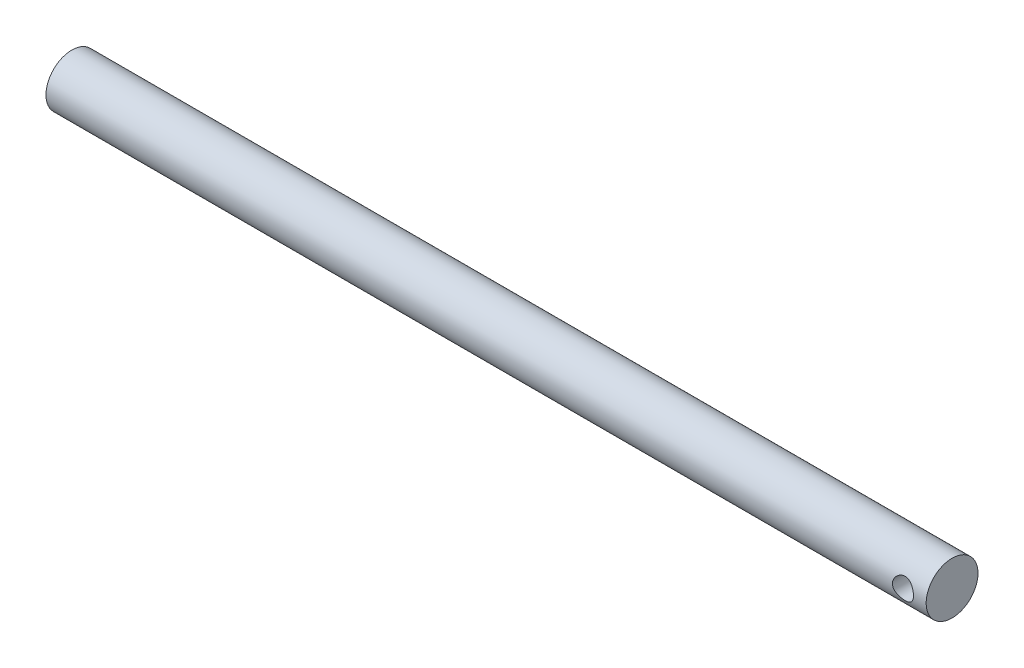
SolidWorks part; units mm, degrees
ref_plane "Front Plane" through (0, 0, 0) normal (0, 0, 1) x (1, 0, 0)
ref_plane "Top Plane" through (0, 0, 0) normal (0, 1, 0) x (1, 0, 0)
ref_plane "Right Plane" through (0, 0, 0) normal (1, 0, 0) x (0, 0, -1)
sketch "Sketch1" plane through (0, 0, 0) normal (1, 0, 0) x (0, 0, -1)
  circle A0 centre (0, 0) radius 9.906
  dimension "D1" = 19.812
extrude "Boss-Extrude1" add sketch "Sketch1" along normal blind 336.55
sketch "Sketch2" plane through (336.55, 0, 0) normal (1, 0, 0) x (0, 0, -1)
  line L0 (-9.906, 0) -> (0, 0)
  circle A0 centre (0, 0) radius 9.906 construction
  point P0 (-9.906, 0)
  point P3 (0, 0)
ref_plane "Plane1" through (336.55, 0, 9.906) normal (0, 0, 1) x (1, 0, 0)
sketch "Sketch3" plane through (336.55, 0, 9.906) normal (0, 0, 1) x (1, 0, 0)
  circle A0 centre (-8.89, 0) radius 4.0132
  point P2 (0, 0)
  dimension "D2" = 8.0264
  dimension "D1" = 8.89
extrude "Cut-Extrude1" cut sketch "Sketch3" against normal through all
